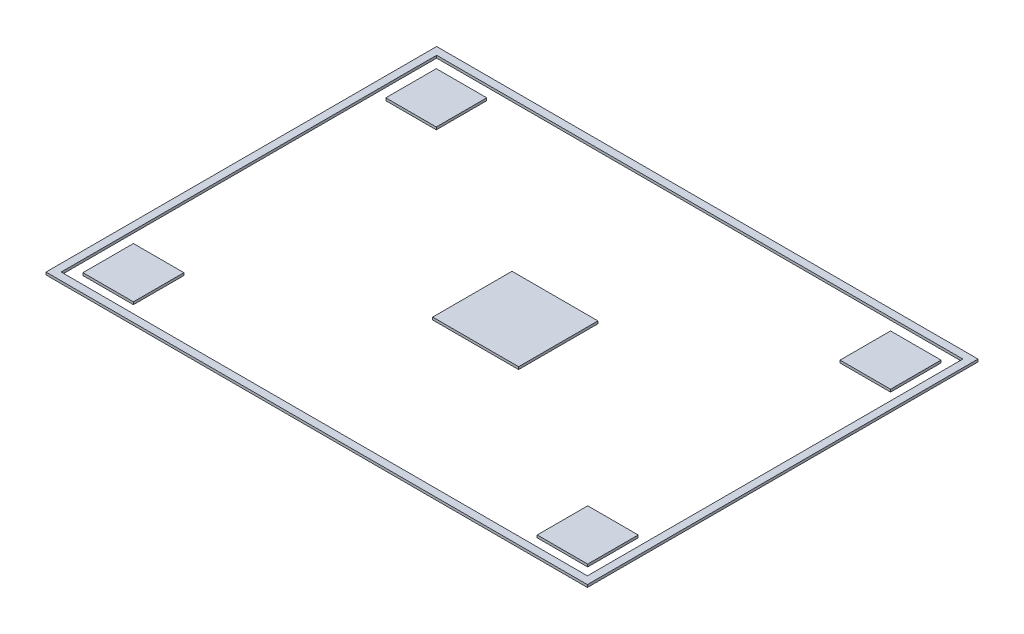
SolidWorks part; units mm, degrees
ref_plane "前视基准面" through (0, 0, 0) normal (0, 0, 1) x (1, 0, 0)
ref_plane "上视基准面" through (0, 0, 0) normal (0, 1, 0) x (1, 0, 0)
ref_plane "右视基准面" through (0, 0, 0) normal (1, 0, 0) x (0, 0, -1)
other "Configuration Table"
sketch "草图1" plane through (0, 0, 0) normal (0, 1, 0) x (1, 0, 0)
  line L0 (180, 0) -> (180, -20)
  line L1 (0, 0) -> (20, 0)
  line L2 (0, 0) -> (0, -20)
  line L3 (0, -20) -> (20, -20)
  line L4 (20, 0) -> (20, -20)
  line L5 (180, 0) -> (200, 0)
  line L6 (200, 0) -> (200, -20)
  line L7 (180, -20) -> (200, -20)
  line L8 (180, 120) -> (180, 100)
  line L9 (180, 120) -> (200, 120)
  line L10 (200, 120) -> (200, 100)
  line L11 (180, 100) -> (200, 100)
  line L12 (0, 120) -> (0, 100)
  line L13 (0, 120) -> (20, 120)
  line L14 (20, 120) -> (20, 100)
  line L15 (0, 100) -> (20, 100)
  line L16 (-7.5324, 127.6771) -> (206.9676, 127.6771)
  line L17 (84.5254, 65.4798) -> (118.5769, 65.4798)
  line L18 (84.5254, 65.4798) -> (84.5254, 34.0477)
  line L19 (84.5254, 34.0477) -> (118.5769, 34.0477)
  line L20 (118.5769, 65.4798) -> (118.5769, 34.0477)
  line L21 (-4.5324, 124.6771) -> (203.9676, 124.6771)
  line L22 (-4.5324, 124.6771) -> (-4.5324, -24.1018)
  line L23 (-4.5324, -24.1018) -> (203.9676, -24.1018)
  line L24 (203.9676, 124.6771) -> (203.9676, -24.1018)
  line L25 (206.9676, 127.6771) -> (206.9676, -27.1018)
  line L26 (-7.5324, -27.1018) -> (206.9676, -27.1018)
  line L27 (-7.5324, 127.6771) -> (-7.5324, -27.1018)
  dimension "D1" = 20
  dimension "D2" = 20
  dimension "D5" = 3
  dimension "D3" = 2
  dimension "D4" = 2
extrude "凸台-拉伸1" add sketch "草图1" along normal blind 1 contours L16 L27 L26 L25 L21 L24 L23 L22 | L12 L15 L14 L13 | L4 L1 L2 L3 | L20 L17 L18 L19 | L8 L11 L10 L9 | L0 L7 L6 L5
